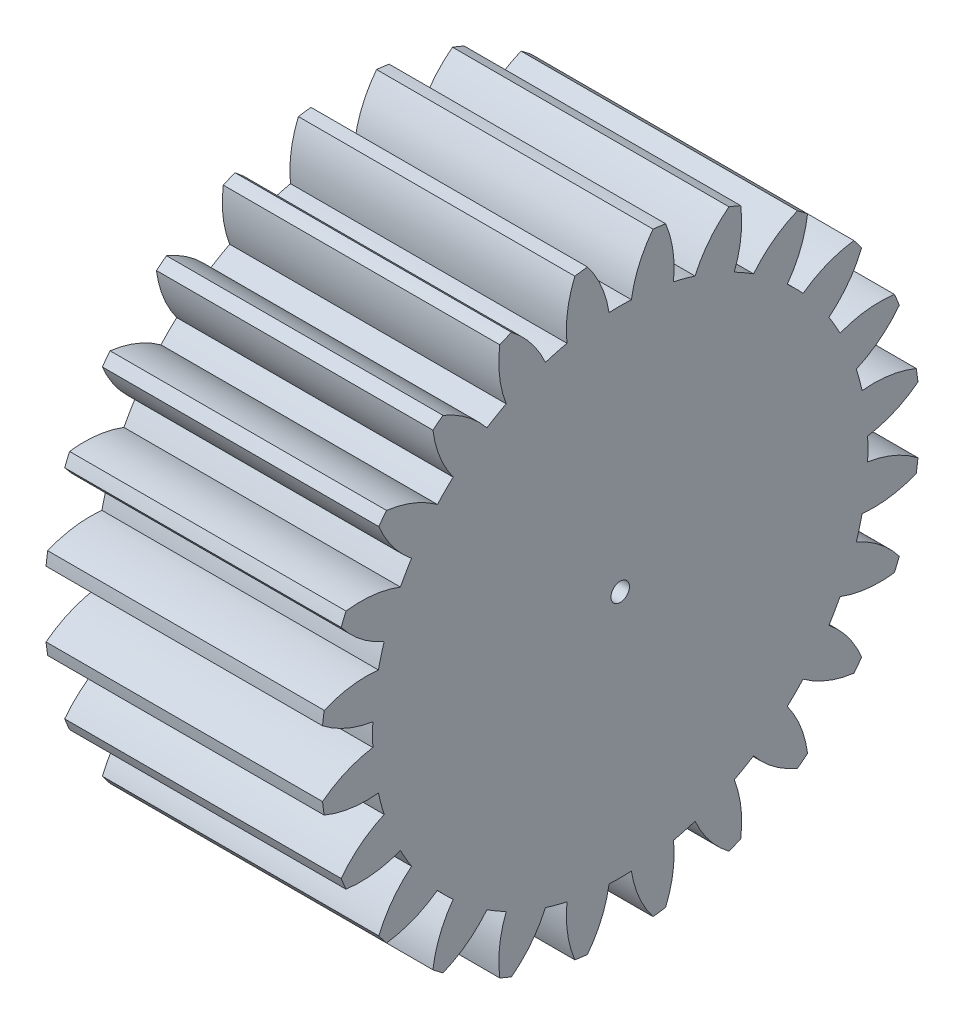
SolidWorks part; units mm, degrees
ref_plane "Plane1" through (0, 0, 0) normal (0, 0, 1) x (1, 0, 0)
ref_plane "Plane2" through (0, 0, 0) normal (0, 1, 0) x (1, 0, 0)
ref_plane "Plane3" through (0, 0, 0) normal (1, 0, 0) x (0, 0, -1)
sketch "HoldingSke" plane through (0, 0, 0) normal (0, 1, 0) x (1, 0, 0)
  line L0 (0, 0) -> (0.9135, -0.4067)
  line L1 (-15, 0) -> (100, 0) construction
  line L2 (0, 0) -> (-2.1039, 2.3779)
  line L3 (0, 0) -> (-11.863, 4.5341)
  line L4 (0, 0) -> (7.8894, 3.5126)
  line L5 (0, 0) -> (-46.8476, -17.4728)
  line L6 (0, 0) -> (-9.9476, -6.7116)
  line L7 (-2.1039, 2.3779) -> (8.6586, 51.2059)
  line L8 (-76.2, 54.61) -> (-76.1, 54.61)
  line L9 (-71.009, 38.7566) -> (-53.1078, 45.2721)
  line L10 (-76.2, 71.12) -> (104.1128, 71.12)
  line L11 (0, 0) -> (-12, 0)
  line L12 (-76.2, 101.6) -> (-76.162, 101.6)
  line L13 (24.9733, 27.94) -> (52.9518, 28.4284)
  line L14 (24.9733, 27.94) -> (24.9743, 27.94)
  line L15 (24.9733, 27.94) -> (100.4006, 29.5858)
  line L16 (-63.627, -1) -> (-12.827, -1)
  circle A0 centre (0, 0) radius 0.4
  circle A1 centre (0, 0) radius 10.749
  circle A2 centre (0, 0) radius 37.5
  circle A3 centre (0, 0) radius 0.4
  dimension "MHD" = 21.498
  dimension "Hub_dia" = 75
  dimension "Bore" = 0.8
  dimension "MBD" = 0.8
  dimension "Num_teeth" = 24
  dimension "Pitch" = 1
  dimension "Overall_len" = 50
  dimension "Show_teeth" = 24
  dimension "Thickness" = 12
  dimension "OAL" = 50.0001
  dimension "T_dim" = 0.1
  dimension "Ap" = 20
  dimension "H" = 19.05
  dimension "Pitch_radius" = 180.3128
  dimension "Width" = 12
  dimension "Backlash" = 0.038
  dimension "Addendum_fac" = 1
  dimension "Dedendum_fac" = 1.25
  dimension "Clearance_fac" = 0.25
  dimension "Dedendum_add" = 0.001
  dimension "Module" = 1
sketch "BasProSke" plane through (0, 0, 0) normal (0, 1, 0) x (1, 0, 0)
  line L0 (-10, 0) -> (60, 0) construction
  line L1 (0, 0) -> (0, 13)
  line L2 (0, 0) -> (12, 0)
  line L3 (12, 0) -> (12, 13)
  line L4 (12, 13) -> (0, 13)
  dimension "Thickness" = 12
  dimension "Diameter" = 26
revolve "Base-Revolve" add sketch "BasProSke" angle 360 about L0
sketch "TooCutSke" plane through (0, 0, 0) normal (1, 0, 0) x (0, 0, -1)
  line L1 (0, 0) -> (0, 107) construction
  line L2 (0, 0) -> (-0.8513, 11.9698) construction
  line L3 (0, 0) -> (-3.127, 23.752) construction
  line L4 (-0.8513, 11.9698) -> (-1.5635, 11.876) construction
  arc A0 (0.4834, 10.7381) -> (-0.4834, 10.7381) centre (0, 0) ccw
  arc A1 (1.4409, 12.9455) -> (-1.4409, 12.9455) centre (0, 0) ccw
  circle A2 centre (0, 0) radius 12 construction
  circle A3 centre (0, 0) radius 11.2763 construction
  arc A4 (-0.4834, 10.7381) -> (-1.4409, 12.9455) centre (-5.2252, 9.9926) ccw
  arc A5 (1.4409, 12.9455) -> (0.4834, 10.7381) centre (5.2252, 9.9926) ccw
  dimension "Root_dia" = 21.498
  dimension "Overcut_dia" = 26.0508
  dimension "Pitch_dia" = 24
  dimension "Base_dia" = 22.5526
  dimension "Flank_rad" = 4.8
  dimension "Half_ang" = 7.5
  dimension "Half_CT" = 0.7183
extrude "ToothCut" cut sketch "TooCutSke" along normal through all
fillet "Breaks" [suppressed] radius 0.02
fillet "RootFillets" [suppressed] radius 0.251
pattern_circular "TeethCuts" count 24 every 15 about axis through (-10, 0, 0) along (1, 0, 0) of "ToothCut", "RootFillets", "Breaks"
sketch "HubNeaOneSke" plane through (0, 0, 0) normal (-1, 0, 0) x (0, 0, 1)
  circle A0 centre (0, 0) radius 10.749
  dimension "Diameter" = 21.498
extrude "HubNearOne" [suppressed] add sketch "HubNeaOneSke" along normal blind 38.0001
sketch "HubNeaBotSke" plane through (0, 0, 0) normal (-1, 0, 0) x (0, 0, 1)
  circle A0 centre (0, 0) radius 10.749
  dimension "Diameter" = 21.498
extrude "HubNearBoth" [suppressed] add sketch "HubNeaBotSke" along normal blind 19
ref_plane "FarPln" through (12, 0, 0) normal (1, 0, 0) x (0, 0, -1)
sketch "HubFarSke" plane through (12, 0, 0) normal (1, 0, 0) x (0, 0, -1)
  circle A0 centre (0, 0) radius 10.749
  dimension "Diameter" = 21.498
extrude "HubFar" [suppressed] add sketch "HubFarSke" along normal blind 19
sketch "BorSke" plane through (0, 0, 0) normal (1, 0, 0) x (0, 0, -1)
  circle A0 centre (0, 0) radius 0.4
  dimension "Diameter" = 0.8
extrude "Bore" cut sketch "BorSke" along normal mid plane 100.0001
sketch "KeySke" plane through (0, 0, 0) normal (1, 0, 0) x (0, 0, -1)
  line L0 (-0.05, 0) -> (-0.05, 0.5)
  line L1 (-0.05, 0.5) -> (0.05, 0.5)
  line L2 (0.05, 0.5) -> (0.05, 0)
  line L3 (0, 0) -> (0, 34) construction
  line L4 (-0.05, 0) -> (0.05, 0)
  dimension "Offset" = 0.5
  dimension "Width" = 0.1
extrude "Keyway" [suppressed] cut sketch "KeySke" along normal mid plane 100.0001
pattern_circular "Keyway2" [suppressed] count 2 every 90 about axis through (-10, 0, 0) along (1, 0, 0)
scale "Scale1" scale about centroid uniform scaling yes scale factor 2
equation "' \"Module@HoldingSke\" = 6.35"
equation "' \"Num_teeth@HoldingSke\" = 12"
equation "' \"Ap@HoldingSke\" =  20"
equation "' \"Ap@HoldingSke\" = 20"
equation "' \"Width@HoldingSke\" = 0.5 * 25.4"
equation "' \"Hub_dia@HoldingSke\"= 1 * 25.4"
equation "' \"Hub_dia@HoldingSke\" = 1 * 25.4"
equation "' \"Overall_len@HoldingSke\" = 1.0 * 25.4"
equation "' \"Bore@HoldingSke\" = 0.75 * 25.4"
equation "' \"T_dim@HoldingSke\" = 0.1 * 25.4"
equation "' \"Width@KeySke\" = 0.25 * 25.4"
equation "' \"Show_teeth@HoldingSke\" = 13"
equation "' \"Backlash@HoldingSke\" = 0.009 * 25.4"
equation "' \"Addendum_fac@HoldingSke\" = 1.0"
equation "' \"Dedendum_fac@HoldingSke\" = 1.25"
equation "' \"Dedendum_add@HoldingSke\" = 0.00005 * 25.4"
equation "' \"Clearance_fac@HoldingSke\" = 0.25"
equation "\"Pitch@HoldingSke\" = 1 / \"Module@HoldingSke\""
equation "\"Overcut_dia@TooCutSke\" = (\"Num_teeth@HoldingSke\" + 2 * \"Addendum_fac@HoldingSke\") / \"Pitch@HoldingSke\" + 0.002 * 25.4"
equation "\"Pitch_dia@TooCutSke\" = \"Num_teeth@HoldingSke\" / \"Pitch@HoldingSke\""
equation "\"Base_dia@TooCutSke\" = \"Num_teeth@HoldingSke\" / \"Pitch@HoldingSke\" * cos((\"Ap@HoldingSke\"  * 3.14159265 / 180))"
equation "\"Root_dia@TooCutSke\" = (\"Num_teeth@HoldingSke\" + 2) / \"Pitch@HoldingSke\" - 2 * (\"Addendum_fac@HoldingSke\" + \"Dedendum_fac@HoldingSke\") / \"Pitch@HoldingSke\" - \"Dedendum_add@HoldingSke\" * 2"
equation "\"Half_ang@TooCutSke\" = 180 / \"Num_teeth@HoldingSke\""
equation "\"Half_CT@TooCutSke\" = \"Num_teeth@HoldingSke\" / \"Pitch@HoldingSke\" * sin((3.14159265 / 2 / \"Num_teeth@HoldingSke\")) / 2 - 7 * \"Backlash@HoldingSke\" / 4"
equation "\"Flank_rad@TooCutSke\" = \"Num_teeth@HoldingSke\" / \"Pitch@HoldingSke\" / 5"
equation "\"Radius@RootFillets\" = \"Clearance_fac@HoldingSke\" / \"Pitch@HoldingSke\" + \"Dedendum_add@HoldingSke\""
equation "\"Break_rad@Breaks\" = 0.02 / \"Pitch@HoldingSke\""
equation "\"Thickness@HoldingSke\" = \"Width@HoldingSke\""
equation "\"OAL@HoldingSke\" = \"Thickness@HoldingSke\""
equation "\"MHD@HoldingSke\" = (\"Num_teeth@HoldingSke\" + 2) / \"Pitch@HoldingSke\" - 2 * (\"Addendum_fac@HoldingSke\" + \"Dedendum_fac@HoldingSke\")  / \"Pitch@HoldingSke\" - \"Dedendum_add@HoldingSke\" * 2"
equation "\"MBD@HoldingSke\" = (\"Num_teeth@HoldingSke\" + 2) / \"Pitch@HoldingSke\" - 2 * (\"Addendum_fac@HoldingSke\" + \"Dedendum_fac@HoldingSke\")  / \"Pitch@HoldingSke\" - \"Dedendum_add@HoldingSke\" * 2 - 0.002 * 25.4"
equation "\"MHD@HoldingSke\" = ((sgn( \"MHD@HoldingSke\" - \"Hub_dia@HoldingSke\" )-1)*( \"MHD@HoldingSke\" - \"Hub_dia@HoldingSke\" ))/-2+ \"Hub_dia@HoldingSke\""
equation "\"MBD@HoldingSke\" = ((sgn( \"MBD@HoldingSke\" - \"Bore@HoldingSke\" )-1)*( \"MBD@HoldingSke\" - \"Bore@HoldingSke\" ))/-2+ \"Bore@HoldingSke\""
equation "\"OAL@HoldingSke\" = ((sgn( \"OAL@HoldingSke\" - \"Overall_len@HoldingSke\" )+1)*( \"OAL@HoldingSke\" - \"Overall_len@HoldingSke\" ))/2 + \"Overall_len@HoldingSke\" + 0.000002 * 25.4"
equation "\"Num_teeth@TeethCuts\" = int( \"Show_teeth@HoldingSke\" ) + 1"
equation "\"Num_teeth@TeethCuts\" = ((sgn( \"Num_teeth@TeethCuts\" - \"Num_teeth@HoldingSke\" )-1)*( \"Num_teeth@TeethCuts\" - \"Num_teeth@HoldingSke\" ))/-2+ \"Num_teeth@HoldingSke\""
equation "\"Num_teeth@TeethCuts\" = ((sgn( \"Num_teeth@TeethCuts\" - 2.0)+1)*( \"Num_teeth@TeethCuts\" - 2.0))/2 +2.0"
equation "\"Angle@TeethCuts\" = 360.0 / \"Num_teeth@HoldingSke\""
equation "\"Diameter@BasProSke\" = (\"Num_teeth@HoldingSke\" + 2 * \"Addendum_fac@HoldingSke\") / \"Pitch@HoldingSke\""
equation "\"Thickness@BasProSke\"  = \"Thickness@HoldingSke\""
equation "' \"Fillet_rad@BasProSke\" =  \"Thickness@HoldingSke\" * 0.05"
equation "' \"Fillet_rad@BasProSke\" = \"Thickness@HoldingSke\" * 0.05"
equation "\"MHD@HoldingSke\" = ((sgn( \"MHD@HoldingSke\" - \"Root_dia@TooCutSke\" )-1)*( \"MHD@HoldingSke\" - \"Root_dia@TooCutSke\" ))/-2+ \"Root_dia@TooCutSke\""
equation "\"Diameter@HubNeaOneSke\" = \"MHD@HoldingSke\""
equation "\"Length@HubNearOne\" = \"OAL@HoldingSke\" - \"Thickness@BasProSke\""
equation "\"Diameter@HubNeaBotSke\" = \"MHD@HoldingSke\""
equation "\"Length@HubNearBoth\" = ( \"OAL@HoldingSke\" - \"Thickness@BasProSke\" ) / 2.0"
equation "\"Thickness@FarPln\" = \"Thickness@BasProSke\""
equation "\"Diameter@HubFarSke\" = \"MHD@HoldingSke\""
equation "\"Length@HubFar\" = ( \"OAL@HoldingSke\" - \"Thickness@BasProSke\" ) / 2.0"
equation "\"Diameter@BorSke\" = \"MBD@HoldingSke\""
equation "\"D1@Bore\" = \"OAL@HoldingSke\" * 2.0"
equation "\"D1@Keyway\" = \"OAL@HoldingSke\" * 2.0"
equation "\"Offset@KeySke\" = \"T_dim@HoldingSke\" + \"MBD@HoldingSke\" / 2.0"
